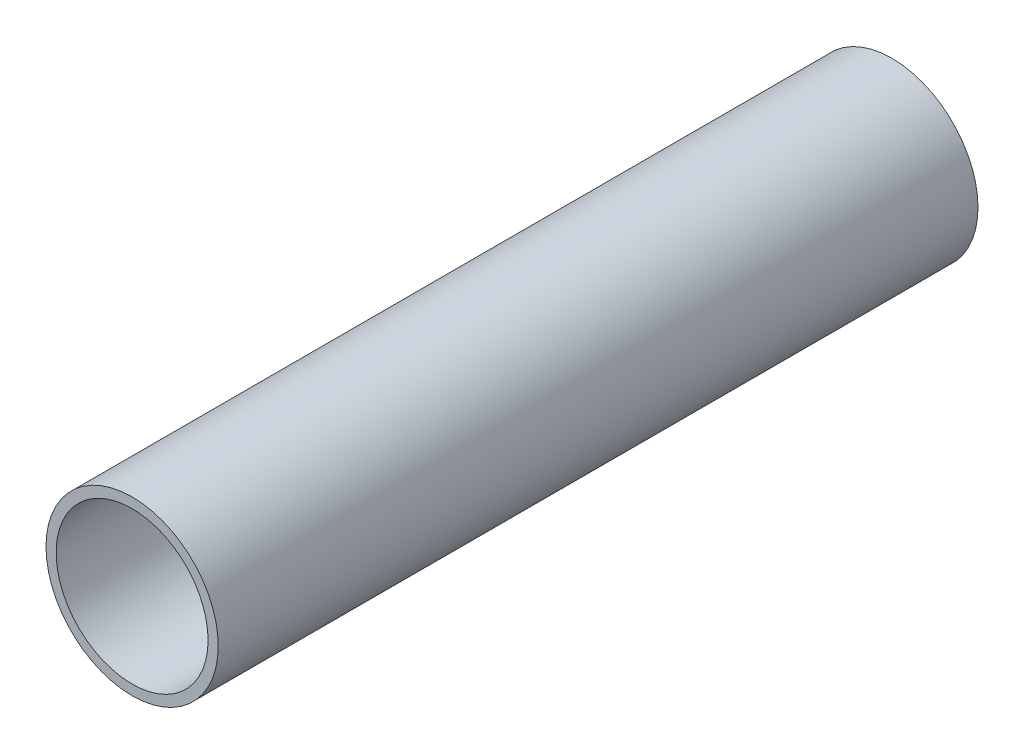
SolidWorks part; units mm, degrees
ref_plane "Front Plane" through (0, 0, 0) normal (0, 0, 1) x (1, 0, 0)
ref_plane "Top Plane" through (0, 0, 0) normal (0, 1, 0) x (1, 0, 0)
ref_plane "Right Plane" through (0, 0, 0) normal (1, 0, 0) x (0, 0, -1)
sketch "Sketch1" plane through (0, 0, 0) normal (0, 0, 1) x (1, 0, 0)
  circle A0 centre (0, 0) radius 15
  circle A1 centre (0, 0) radius 17
  dimension "D1" = 30
  dimension "D2" = 2
extrude "Boss-Extrude1" add sketch "Sketch1" along normal mid plane 150 contours A1 A0
